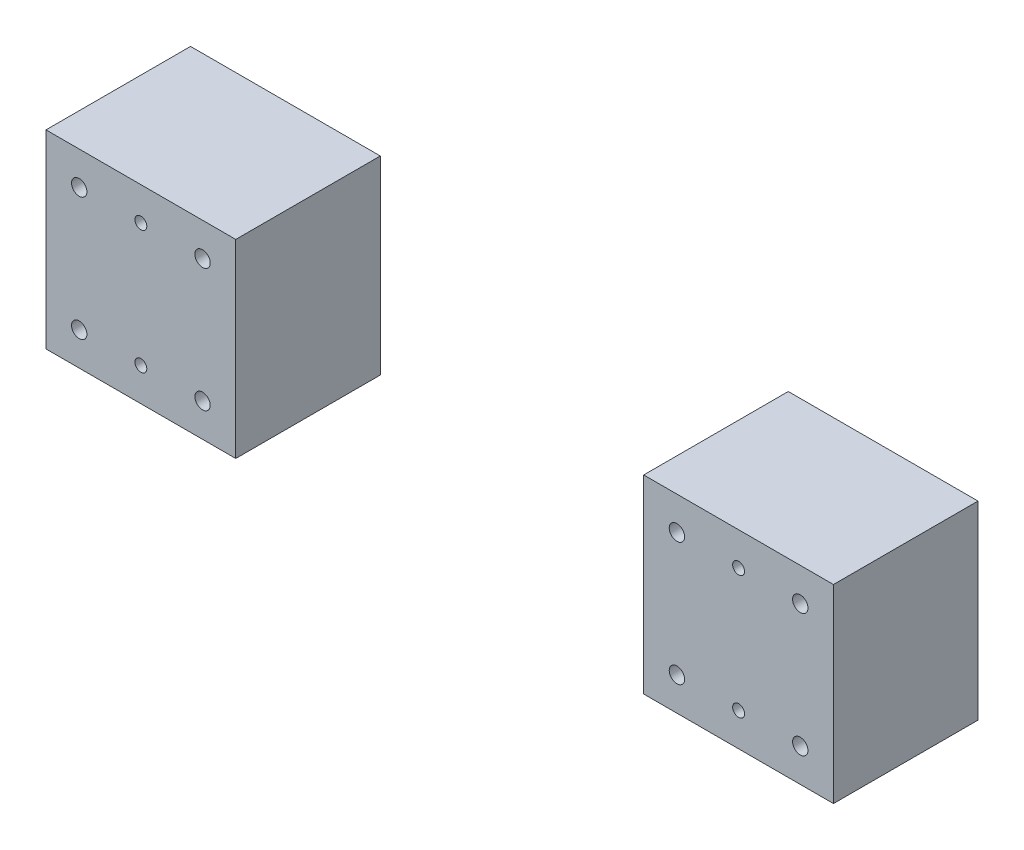
SolidWorks part; units mm, degrees
ref_plane "Front Plane" through (0, 0, 0) normal (0, 0, 1) x (1, 0, 0)
ref_plane "Top Plane" through (0, 0, 0) normal (0, 1, 0) x (1, 0, 0)
ref_plane "Right Plane" through (0, 0, 0) normal (1, 0, 0) x (0, 0, -1)
sketch "Sketch1" plane through (0, 0, 0) normal (0, 0, 1) x (-1, 0, 0)
  line L1 (0, 0) -> (-40, 0)
  line L2 (0, 0) -> (0, -40)
  line L3 (0, -40) -> (-40, -40)
  line L4 (-40, 0) -> (-40, -40)
  line L5 (-126, 0) -> (-166, 0)
  line L6 (-126, 0) -> (-126, -40)
  line L7 (-126, -40) -> (-166, -40)
  line L8 (-166, 0) -> (-166, -40)
  circle A8 centre (-159, -7) radius 1.621
  circle A9 centre (-133, -7) radius 1.621
  circle A10 centre (-133, -33) radius 1.621
  circle A11 centre (-159, -33) radius 1.621
  circle A12 centre (-33, -7) radius 1.621
  circle A13 centre (-7, -7) radius 1.621
  circle A14 centre (-7, -33) radius 1.621
  circle A15 centre (-33, -33) radius 1.621
  dimension "D25" = 3.242
  dimension "D26" = 3.242
  dimension "D27" = 3.242
  dimension "D28" = 3.242
  dimension "D29" = 3.242
  dimension "D30" = 3.242
  dimension "D31" = 3.242
  dimension "D32" = 3.242
  dimension "D1" = 26
  dimension "D2" = 26
  dimension "D3" = 26
  dimension "D4" = 26
  dimension "D5" = 40
  dimension "D6" = 40
  dimension "D7" = 7
  dimension "D8" = 7
  dimension "D9" = 7
  dimension "D10" = 100
  dimension "D11" = 26
  dimension "D12" = 26
  dimension "D13" = 100
  dimension "D14" = 26
  dimension "D15" = 26
  dimension "D16" = 40
  dimension "D17" = 40
  dimension "D18" = 7
  dimension "D19" = 7
  dimension "D20" = 7
  dimension "D21" = 0
  dimension "D22" = 0
  dimension "D23" = 40
  dimension "D24" = 0
extrude "Boss-Extrude1" add sketch "Sketch1" along normal blind 30.47
sketch "Sketch4" plane through (0, 0, 0) normal (0, 0, -1) x (-1, 0, 0)
  circle A8 centre (-7, 7) radius 4.2
  circle A9 centre (-33, 7) radius 4.2
  circle A10 centre (-7, 33) radius 4.2
  circle A11 centre (-33, 33) radius 4.2
  circle A12 centre (-133, 7) radius 4.2
  circle A13 centre (-133, 33) radius 4.2
  circle A14 centre (-159, 33) radius 4.2
  circle A15 centre (-159, 7) radius 4.2
extrude "Cut-Extrude1" cut sketch "Sketch4" against normal blind 20
sketch "Sketch5" plane through (0, 0, 0) normal (0, 0, -1) x (-1, 0, 0)
  line L0 (0, 40) -> (0, 0) construction
  line L1 (-40, 40) -> (0, 40) construction
  line L2 (-126, 40) -> (-126, 0) construction
  line L3 (-166, 40) -> (-126, 40) construction
  circle A0 centre (-20, 7) radius 1.5
  circle A1 centre (-20, 33) radius 1.5
  circle A2 centre (-146, 7) radius 1.5
  circle A3 centre (-146, 33) radius 1.5
  dimension "D1" = 3
  dimension "D2" = 3
  dimension "D3" = 3
  dimension "D4" = 3
  dimension "D7" = 7
  dimension "D5" = 20
  dimension "D6" = 26
  dimension "D8" = 20
  dimension "D9" = 26
  dimension "D10" = 7
hole_wizard "M3x0.5 Tapped Hole1" positions "3DSketch1" profile "Sketch7" tap size "M3x0.5" standard "Ansi Metric" end condition through all
sketch3d "3DSketch1"
  point P0 (20, 7, 0)
  point P3 (20, 33, 0)
  point P6 (146, 33, 0)
  point P9 (146, 7, 0)
sketch "Sketch7" plane through (20, 7, 0) normal (1, 0, 0) x (0, 1, 0)
  line L0 (0, 0) -> (0, 30.47)
  line L1 (0, 30.47) -> (1.25, 30.47)
  line L2 (1.25, 30.47) -> (1.25, 0)
  line L5 (1.25, 0) -> (0, 0)
  line L11 (0, -6.35) -> (0, 107.95) construction
  dimension "Thru Tap Drill Dia." = 2.5
  dimension "Thru Tap Drill Depth" = 30.47
cosmetic thread "Hole Thread1" parameters "D2"=3
cosmetic thread "Hole Thread2" parameters "D2"=3
cosmetic thread "Hole Thread3" parameters "D2"=3
cosmetic thread "Hole Thread4" parameters "D2"=3
